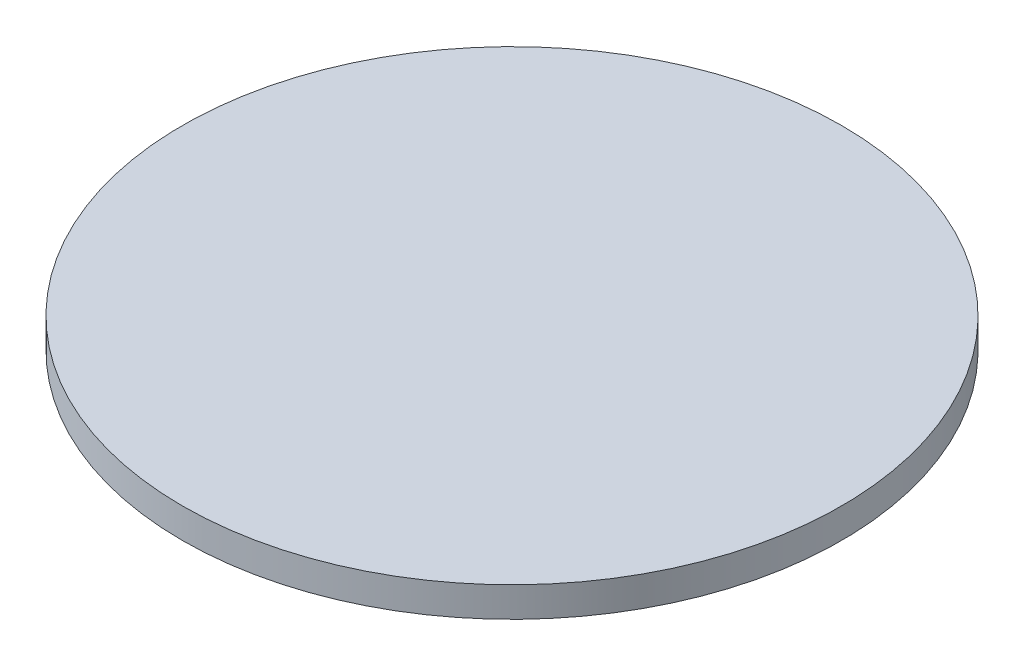
SolidWorks part; units mm, degrees
ref_plane "Front Plane" through (0, 0, 0) normal (0, 0, 1) x (1, 0, 0)
ref_plane "Top Plane" through (0, 0, 0) normal (0, 1, 0) x (1, 0, 0)
ref_plane "Right Plane" through (0, 0, 0) normal (1, 0, 0) x (0, 0, -1)
sketch "Sketch1" plane through (0, 0, 0) normal (0, 1, 0) x (1, 0, 0)
  circle A0 centre (0, 0) radius 33
extrude "Boss-Extrude1" add sketch "Sketch1" along normal blind 3
